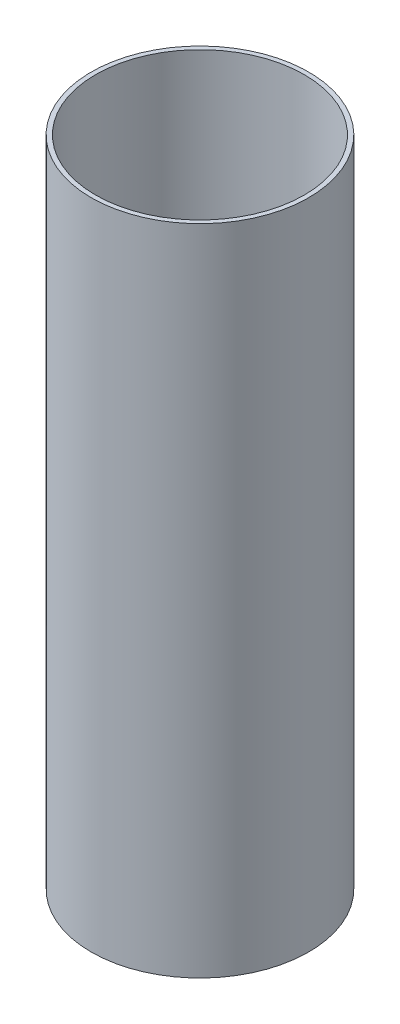
SolidWorks part; units mm, degrees
ref_plane "Front Plane" through (0, 0, 0) normal (0, 0, 1) x (1, 0, 0)
ref_plane "Top Plane" through (0, 0, 0) normal (0, 1, 0) x (1, 0, 0)
ref_plane "Right Plane" through (0, 0, 0) normal (1, 0, 0) x (0, 0, -1)
sketch "Sketch1" plane through (0, 0, 0) normal (0, 1, 0) x (1, 0, 0)
  circle A0 centre (0, 0) radius 38.0746
  circle A1 centre (0, 0) radius 36.5125
  dimension "D1" = 76.1492
  dimension "D2" = 73.025
extrude "Boss-Extrude1" add sketch "Sketch1" along normal blind 228.6
